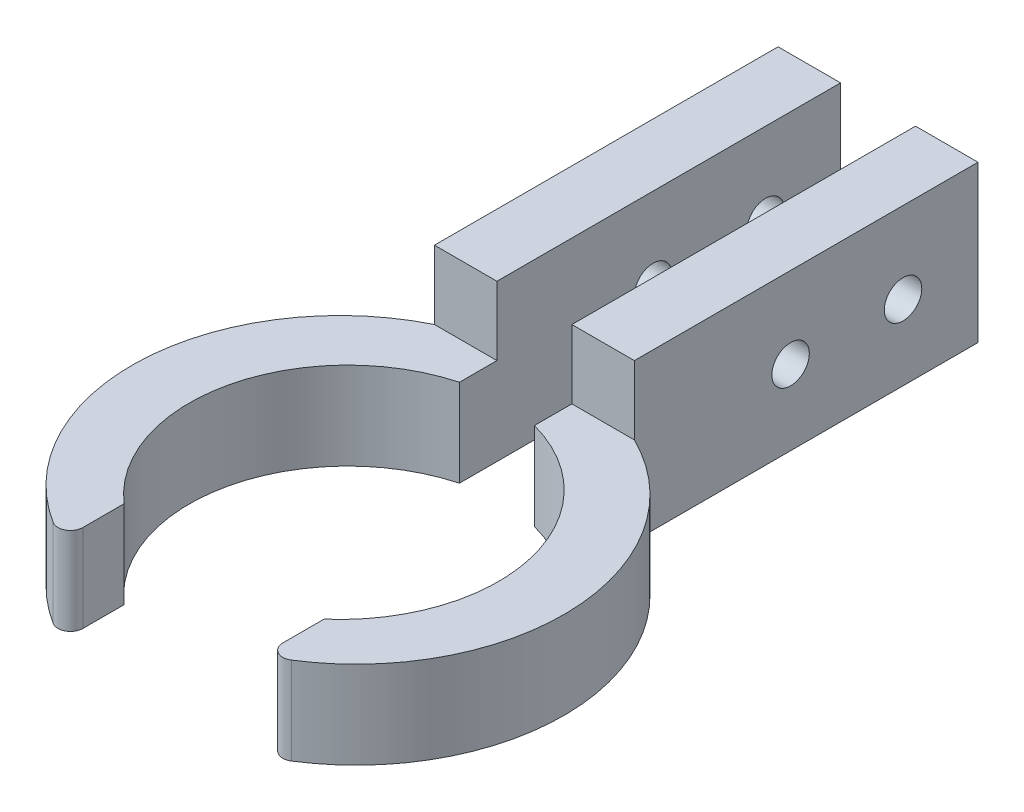
SolidWorks part; units mm, degrees
ref_plane "Alzado" through (0, 0, 0) normal (0, 0, 1) x (1, 0, 0)
ref_plane "Planta" through (0, 0, 0) normal (0, 1, 0) x (1, 0, 0)
ref_plane "Vista lateral" through (0, 0, 0) normal (1, 0, 0) x (0, 0, -1)
sketch "Croquis1" plane through (0, 0, 0) normal (0, 1, 0) x (1, 0, 0)
  line L0 (2.5, -13.75) -> (2.5, -16.75)
  line L1 (5.5, 13.75) -> (5.5, -43.5874) construction
  line L2 (-2.5, -13.75) -> (-2.5, 13.75)
  line L3 (-2.5, 13.75) -> (2.5, 13.75)
  line L4 (2.5, -13.75) -> (2.5, 13.75)
  line L5 (-2.5, -13.75) -> (2.5, 13.75) construction
  line L6 (-2.5, 13.75) -> (2.5, -13.75) construction
  line L7 (2.5, -16.75) -> (2.5, -41.25) construction
  line L8 (-2.5, -38.5874) -> (-2.5, -43.5874)
  line L9 (2.5, -29) -> (-7, -29) construction
  line L10 (8.5, -29) -> (18, -29) construction
  line L11 (8.5, -16.75) -> (8.5, -41.25) construction
  line L12 (13.5, 13.75) -> (8.5, -13.75) construction
  line L13 (13.5, -13.75) -> (8.5, 13.75) construction
  line L14 (13.5, -38.5874) -> (13.5, -43.5874)
  line L15 (8.5, -13.75) -> (8.5, 13.75)
  line L16 (13.5, 13.75) -> (8.5, 13.75)
  line L17 (13.5, -13.75) -> (13.5, 13.75)
  line L18 (8.5, -13.75) -> (8.5, -16.75)
  arc A0 (2.5, -16.75) -> (-2.5, -38.5874) centre (5.8145, -29) ccw
  arc A1 (-2.5, -13.75) -> (-2.5, -43.5874) centre (4.8466, -28.6687) ccw
  arc A2 (13.5, -13.75) -> (13.5, -43.5874) centre (6.1534, -28.6687) cw
  arc A3 (8.5, -16.75) -> (13.5, -38.5874) centre (5.1855, -29) cw
  point P0 (0, 0)
  point P28 (11, 0)
  dimension "D1" = 27.5
  dimension "D2" = 5
  dimension "D3" = 3
  dimension "D4" = 24.5
  dimension "D5" = 9.5
  dimension "D6" = 5
  dimension "D7" = 3
extrude "Saliente-Extruir1" add sketch "Croquis1" along normal blind 7
sketch "Croquis2" plane through (0, 7, 0) normal (0, 1, 0) x (1, 0, 0)
  line L1 (-2.5, -13.75) -> (2.5, -13.75)
  line L2 (-2.5, -13.75) -> (-2.5, 13.75)
  line L3 (-2.5, 13.75) -> (2.5, 13.75)
  line L4 (2.5, -13.75) -> (2.5, 13.75)
  line L5 (13.5, -13.75) -> (8.5, -13.75)
  line L6 (13.5, -13.75) -> (13.5, 13.75)
  line L7 (13.5, 13.75) -> (8.5, 13.75)
  line L8 (8.5, -13.75) -> (8.5, 13.75)
extrude "Saliente-Extruir2" add sketch "Croquis2" along normal blind 5.5
sketch "Croquis3" plane through (13.5, 0, 0) normal (1, 0, 0) x (0, 0, -1)
  line L0 (13.75, 12.5) -> (13.75, 0) construction
  line L1 (-13.75, 0) -> (13.75, 0) construction
  circle A0 centre (7.75, 6) radius 1.5
  circle A1 centre (-1.25, 6) radius 1.5
  dimension "D1" = 3
  dimension "D3" = 9
  dimension "D4" = 3
  dimension "D2" = 6
  dimension "D5" = 6
  dimension "D6" = 6
extrude "Cortar-Extruir1" cut sketch "Croquis3" against normal up to surface (16 mm away) up to face at (-2.5, 6.4, 2.75)
fillet "Redondeo1" radius 1 1 edges at (-2.5, 3.5, 43.5874)
fillet "Redondeo2" radius 1 1 edges at (13.5, 3.5, 43.5874)
